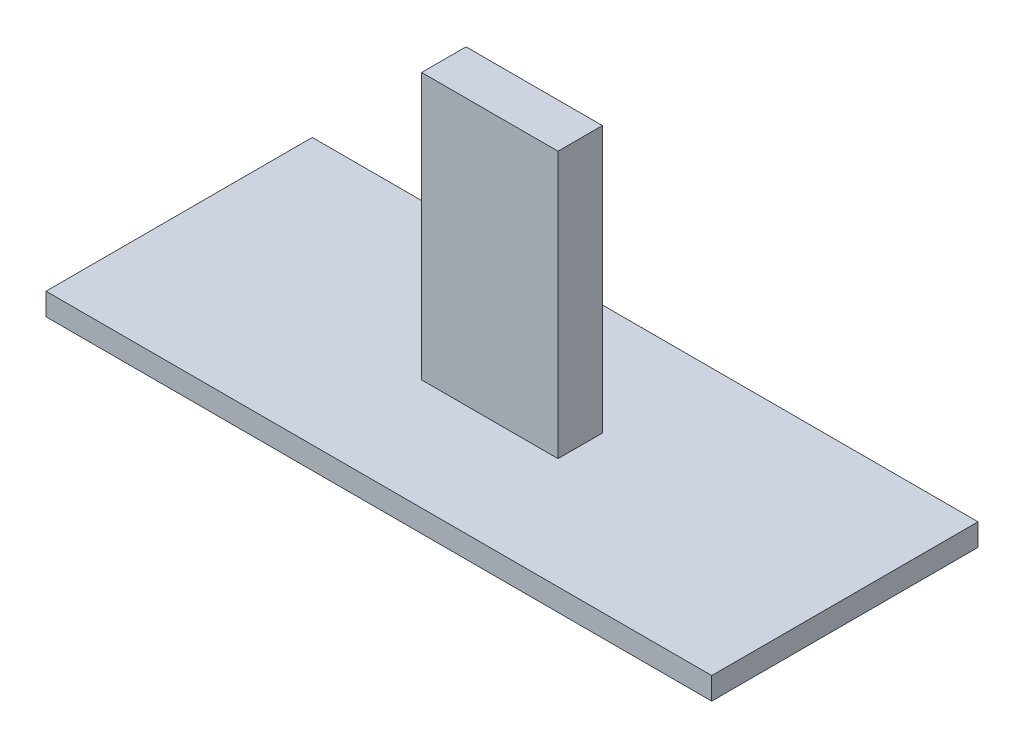
SolidWorks part; units mm, degrees
ref_plane "前视基准面" through (0, 0, 0) normal (0, 0, 1) x (1, 0, 0)
ref_plane "上视基准面" through (0, 0, 0) normal (0, 1, 0) x (1, 0, 0)
ref_plane "右视基准面" through (0, 0, 0) normal (1, 0, 0) x (0, 0, -1)
sketch "草图1" plane through (0, 0, 0) normal (0, 1, 0) x (1, 0, 0)
  line L0 (-212.9255, 0) -> (239.3717, 0) construction
  line L1 (0, -155.6255) -> (0, 159.6941) construction
  line L2 (-118.6687, 0) -> (-118.6687, 60)
  line L3 (-118.6687, 0) -> (31.3313, 0)
  line L4 (-118.6687, 60) -> (31.3313, 60)
  line L5 (31.3313, 0) -> (31.3313, 60)
  dimension "D1" = 150
  dimension "D2" = 60
extrude "凸台-拉伸1" add sketch "草图1" along normal blind 5
sketch "草图2" plane through (0, 5, 0) normal (0, 1, 0) x (1, 0, 0)
  line L3 (-59.0307, 30) -> (31.3313, 30) construction
  line L5 (31.3313, 0) -> (31.3313, 60) construction
  line L6 (-59.0307, 25) -> (-59.0307, 35)
  line L7 (-59.0307, 35) -> (-28.3067, 35)
  line L8 (-28.3067, 25) -> (-28.3067, 35)
  line L9 (-59.0307, 25) -> (-28.3067, 25)
  point P17 (-43.6687, 35)
  point P18 (-28.3067, 30)
  point P19 (-59.0307, 30)
  dimension "D1" = 10
  dimension "D2" = 30.724
extrude "凸台-拉伸2" add sketch "草图2" along normal blind 60
